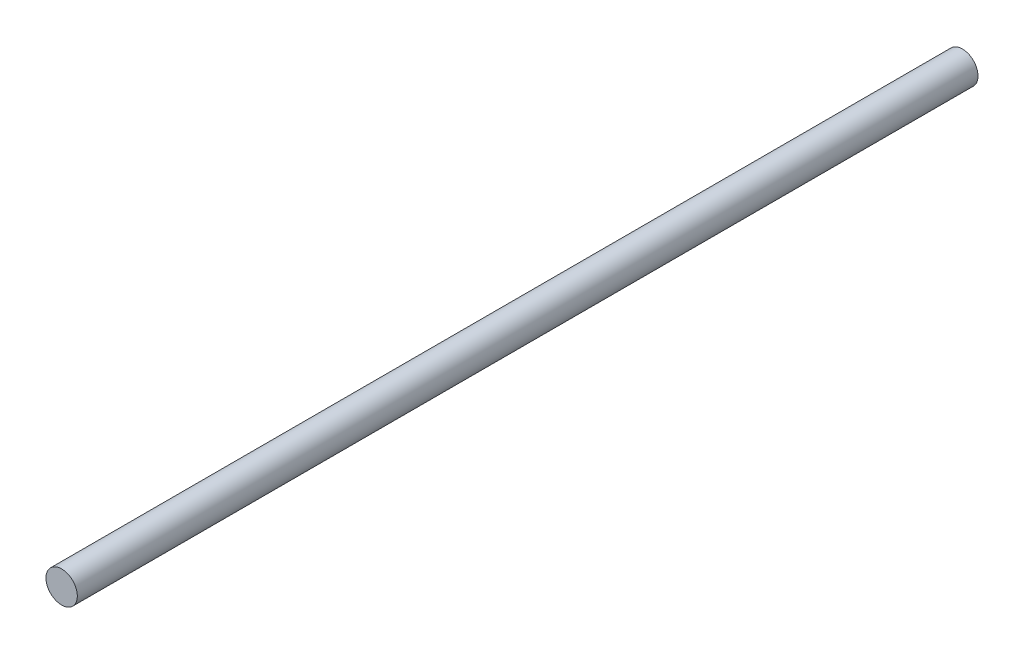
SolidWorks part; units mm, degrees
material "СТ3КП"
ref_plane "Спереди" through (0, 0, 0) normal (0, 0, 1) x (1, 0, 0)
ref_plane "Сверху" through (0, 0, 0) normal (0, 1, 0) x (1, 0, 0)
ref_plane "Справа" through (0, 0, 0) normal (1, 0, 0) x (0, 0, -1)
sketch "Эскиз1" plane through (0, 0, 0) normal (0, 0, 1) x (1, 0, 0)
  circle A0 centre (0, 0) radius 6 construction
  circle A1 centre (0, 0) radius 6
extrude "Бобышка-Вытянуть1" add sketch "Эскиз1" along normal up to surface (172.3 mm away)
mirror "Зеркальное отражение1" about plane through (0, 0, 0) normal (0, 0, 1) of bodies 103
